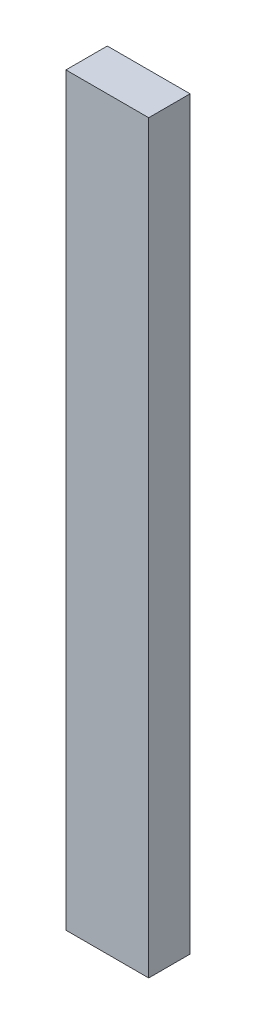
SolidWorks part; units mm, degrees
ref_plane "Front Plane" through (0, 0, 0) normal (0, 0, 1) x (1, 0, 0)
ref_plane "Top Plane" through (0, 0, 0) normal (0, 1, 0) x (1, 0, 0)
ref_plane "Right Plane" through (0, 0, 0) normal (1, 0, 0) x (0, 0, -1)
sketch "Sketch1" plane through (0, 0, 0) normal (0, 0, 1) x (1, 0, 0)
  line L1 (-12.7, -114.3) -> (12.7, -114.3)
  line L2 (-12.7, -114.3) -> (-12.7, 114.3)
  line L3 (-12.7, 114.3) -> (12.7, 114.3)
  line L4 (12.7, -114.3) -> (12.7, 114.3)
  line L5 (-12.7, -114.3) -> (12.7, 114.3) construction
  line L6 (-12.7, 114.3) -> (12.7, -114.3) construction
  point P0 (0, 0)
  dimension "D1" = 25.4
  dimension "D2" = 228.6
extrude "Boss-Extrude1" add sketch "Sketch1" along normal blind 12.7
